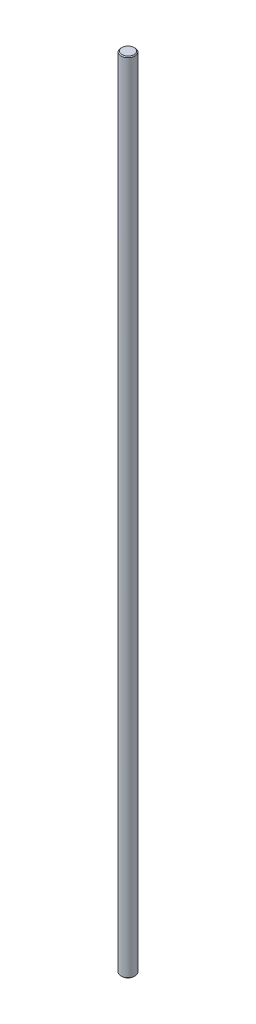
SolidWorks part; units mm, degrees
material "Acero inoxidable al cromo"
ref_plane "Alzado" through (0, 0, 0) normal (0, 0, 1) x (1, 0, 0)
ref_plane "Planta" through (0, 0, 0) normal (0, 1, 0) x (1, 0, 0)
ref_plane "Vista lateral" through (0, 0, 0) normal (1, 0, 0) x (0, 0, -1)
sketch "Croquis1" plane through (0, 0, 0) normal (0, 1, 0) x (1, 0, 0)
  circle A0 centre (0, 0) radius 4
  circle A1 centre (0, 0) radius 3 construction
  dimension "D1" = 8
  dimension "D2" = 6
extrude "Saliente-Extruir1" add sketch "Croquis1" along normal blind 455
chamfer "Chaflán1" distance 0.5 angle 45 2 edges at (0, 0, 4) (0, 455, 4)
